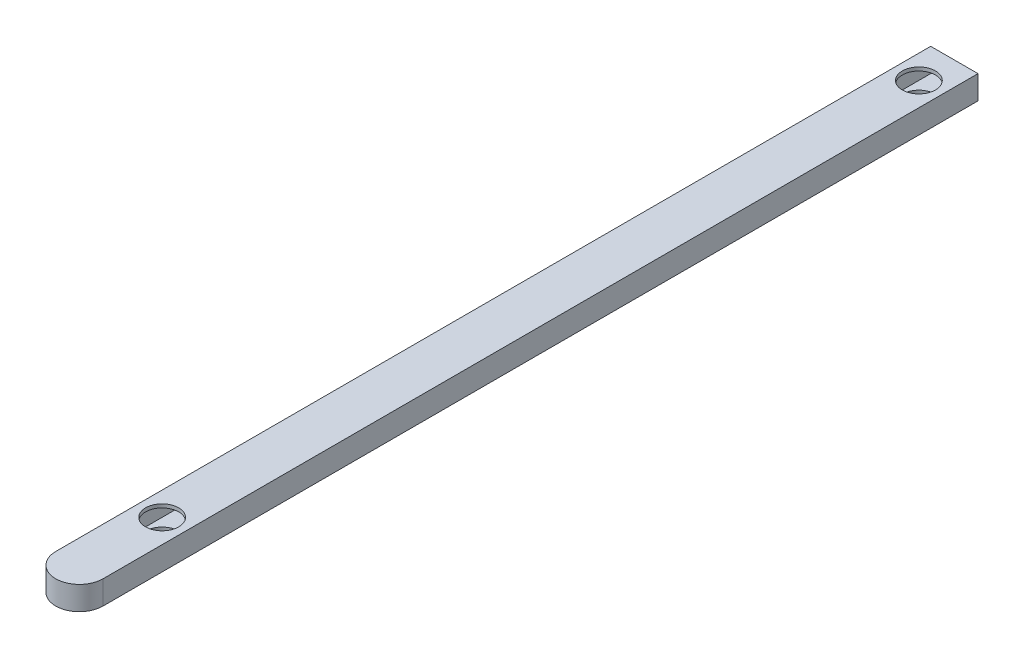
SolidWorks part; units mm, degrees
material "6061 合金"
ref_plane "前视基准面" through (0, 0, 0) normal (0, 0, 1) x (1, 0, 0)
ref_plane "上视基准面" through (0, 0, 0) normal (0, 1, 0) x (1, 0, 0)
ref_plane "右视基准面" through (0, 0, 0) normal (1, 0, 0) x (0, 0, -1)
sketch "草图1" plane through (0, 0, 0) normal (0, 0, 1) x (1, 0, 0)
  line L1 (-10, 5) -> (10, 5)
  line L2 (-10, 5) -> (-10, -5)
  line L3 (-10, -5) -> (10, -5)
  line L4 (10, 5) -> (10, -5)
  line L5 (-10, 5) -> (10, -5) construction
  line L6 (-10, -5) -> (10, 5) construction
  line L7 (-8.5, 3.5) -> (8.5, 3.5)
  line L8 (-8.5, 3.5) -> (-8.5, -3.5)
  line L9 (-8.5, -3.5) -> (8.5, -3.5)
  line L10 (8.5, 3.5) -> (8.5, -3.5)
  line L11 (-8.5, 3.5) -> (8.5, -3.5) construction
  line L12 (-8.5, -3.5) -> (8.5, 3.5) construction
  point P0 (0, 0)
  point P5 (0, 0)
  dimension "D1" = 20
  dimension "D2" = 10
  dimension "D3" = 17
  dimension "D4" = 7
extrude "凸台-拉伸1" add sketch "草图1" along normal blind 370
sketch "草图2" plane through (0, 5, 0) normal (0, 1, 0) x (1, 0, 0)
  line L0 (0, -55) -> (0, 55) construction
  line L1 (-55, 0) -> (55, 0) construction
  circle A0 centre (0, -15) radius 7
  circle A1 centre (0, -335) radius 7
  dimension "D1" = 15
  dimension "D2" = 320
  dimension "D3" = 14
extrude "切除-拉伸1" cut sketch "草图2" against normal blind 10
sketch "草图3" plane through (0, 5, 0) normal (0, 1, 0) x (1, 0, 0)
  line L0 (10, -370) -> (-10, -370) construction
  line L1 (-10, -370) -> (10, -370)
  arc A0 (-10, -370) -> (10, -370) centre (0, -370) ccw
extrude "凸台-拉伸2" add sketch "草图3" against normal blind 10
